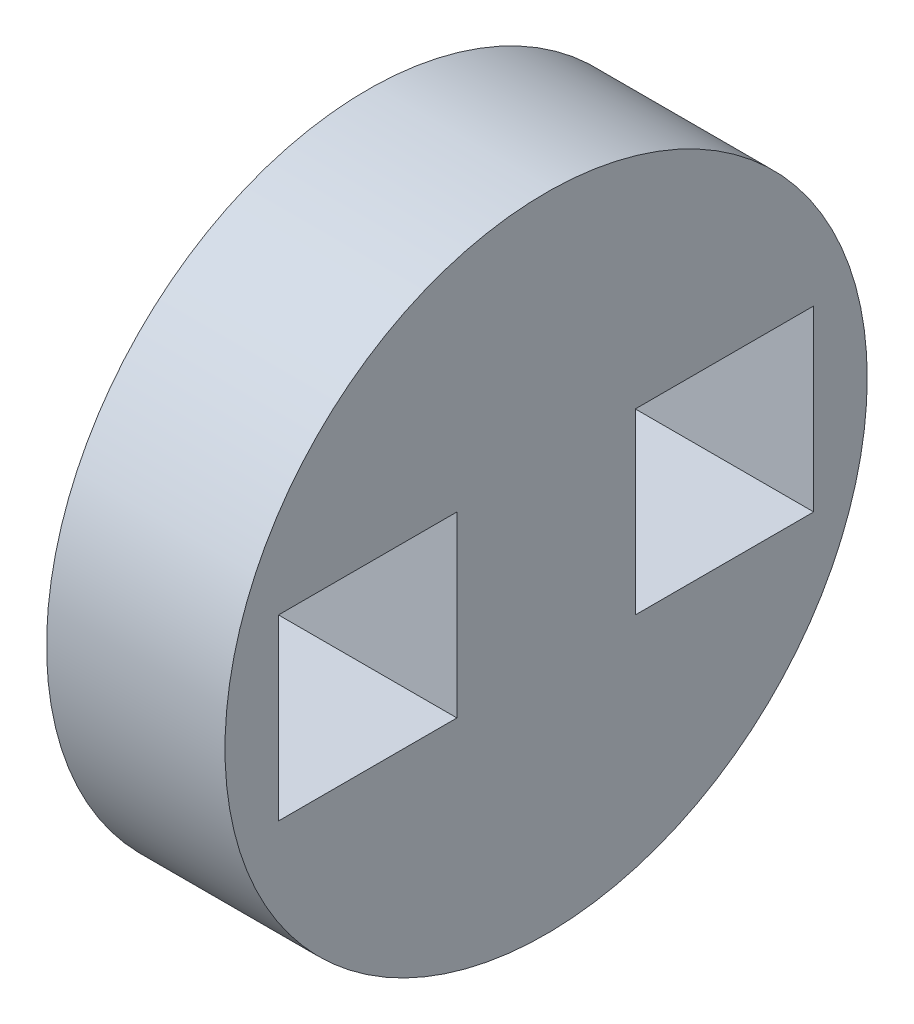
SolidWorks part; units mm, degrees
ref_plane "Front Plane" through (0, 0, 0) normal (0, 0, 1) x (1, 0, 0)
ref_plane "Top Plane" through (0, 0, 0) normal (0, 1, 0) x (1, 0, 0)
ref_plane "Right Plane" through (0, 0, 0) normal (1, 0, 0) x (0, 0, -1)
sketch "Sketch1" plane through (0, 0, 0) normal (1, 0, 0) x (0, 0, -1)
  line L1 (-11.43, 0) -> (11.43, 0) construction
  line L2 (-9.525, 3.175) -> (-3.175, 3.175)
  line L3 (-9.525, 3.175) -> (-9.525, -3.175)
  line L4 (-9.525, -3.175) -> (-3.175, -3.175)
  line L5 (-3.175, 3.175) -> (-3.175, -3.175)
  line L6 (-9.525, 3.175) -> (-3.175, -3.175) construction
  line L7 (-9.525, -3.175) -> (-3.175, 3.175) construction
  line L8 (9.525, 3.175) -> (3.175, 3.175)
  line L9 (9.525, 3.175) -> (9.525, -3.175)
  line L10 (9.525, -3.175) -> (3.175, -3.175)
  line L11 (3.175, 3.175) -> (3.175, -3.175)
  line L12 (9.525, 3.175) -> (3.175, -3.175) construction
  line L13 (9.525, -3.175) -> (3.175, 3.175) construction
  circle A0 centre (0, 0) radius 11.43
  point P0 (-6.35, 0)
  point P11 (6.35, 0)
  dimension "D1" = 3.175
  dimension "D2" = 6.35
  dimension "D3" = 3.175
  dimension "D4" = 6.35
extrude "Boss-Extrude1" add sketch "Sketch1" along normal blind 6.35
